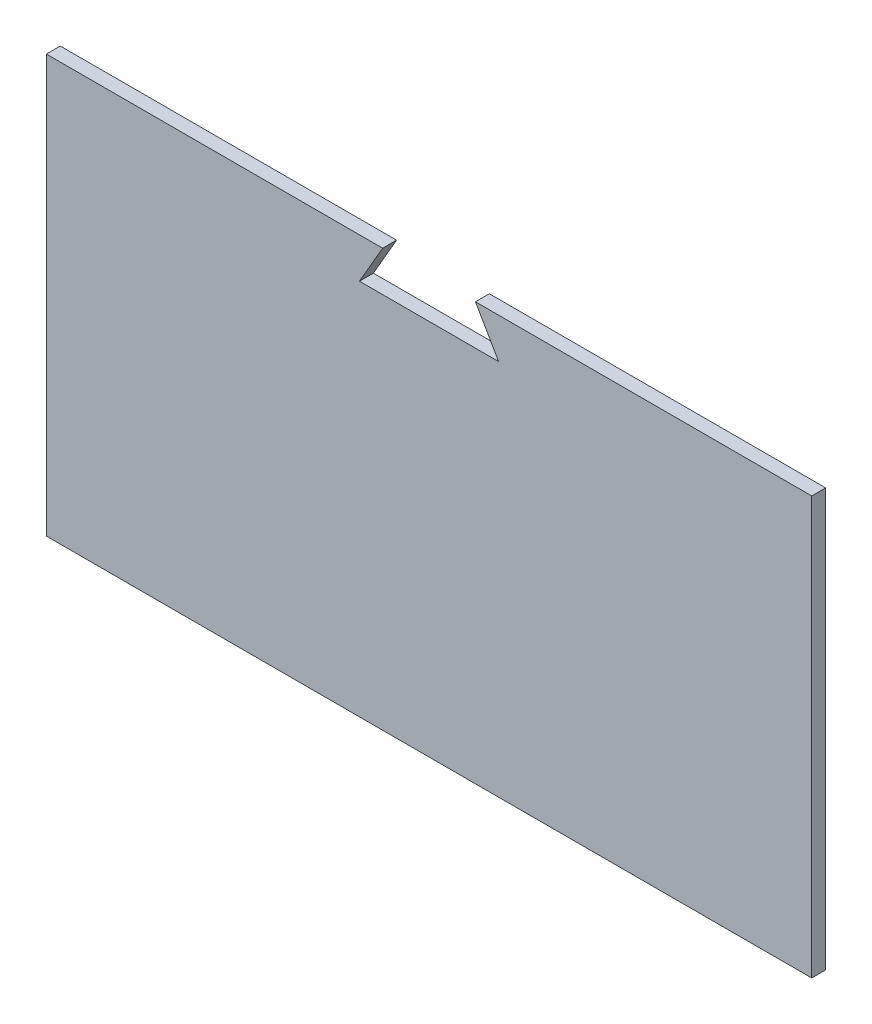
SolidWorks part; units mm, degrees
ref_plane "Front Plane" through (0, 0, 0) normal (0, 0, 1) x (1, 0, 0)
ref_plane "Top Plane" through (0, 0, 0) normal (0, 1, 0) x (1, 0, 0)
ref_plane "Right Plane" through (0, 0, 0) normal (1, 0, 0) x (0, 0, -1)
sketch "Sketch1" plane through (0, 0, 0) normal (0, 0, 1) x (1, 0, 0)
  line L1 (-27.5, -12.5) -> (27.5, -12.5)
  line L2 (-27.5, -12.5) -> (-27.5, 17.5)
  line L3 (-27.5, 17.5) -> (27.5, 17.5)
  line L4 (27.5, -12.5) -> (27.5, 17.5)
  line L5 (-27.5, -12.5) -> (27.5, 17.5) construction
  line L6 (-27.5, 17.5) -> (27.5, -12.5) construction
  point P0 (0, 2.5)
  dimension "D1" = 55
  dimension "D2" = 30
extrude "Boss-Extrude1" add sketch "Sketch1" along normal blind 1
sketch "Sketch2" plane through (0, 0, 1) normal (0, 0, 1) x (1, 0, 0)
  line L0 (0, 17.5) -> (0, -12.5) construction
  line L1 (27.5, 17.5) -> (-27.5, 17.5) construction
  line L2 (-27.5, -12.5) -> (27.5, -12.5) construction
  line L4 (0, 23.2735) -> (-5, 14.6132)
  line L5 (-5, 14.6132) -> (5, 14.6132)
  line L6 (5, 14.6132) -> (0, 23.2735)
  circle A0 centre (0, 17.5) radius 2.8868 construction
  point P6 (0, 0)
  point P11 (5, 17.6132)
  dimension "D1" = 10
extrude "Cut-Extrude1" cut sketch "Sketch2" against normal through all
